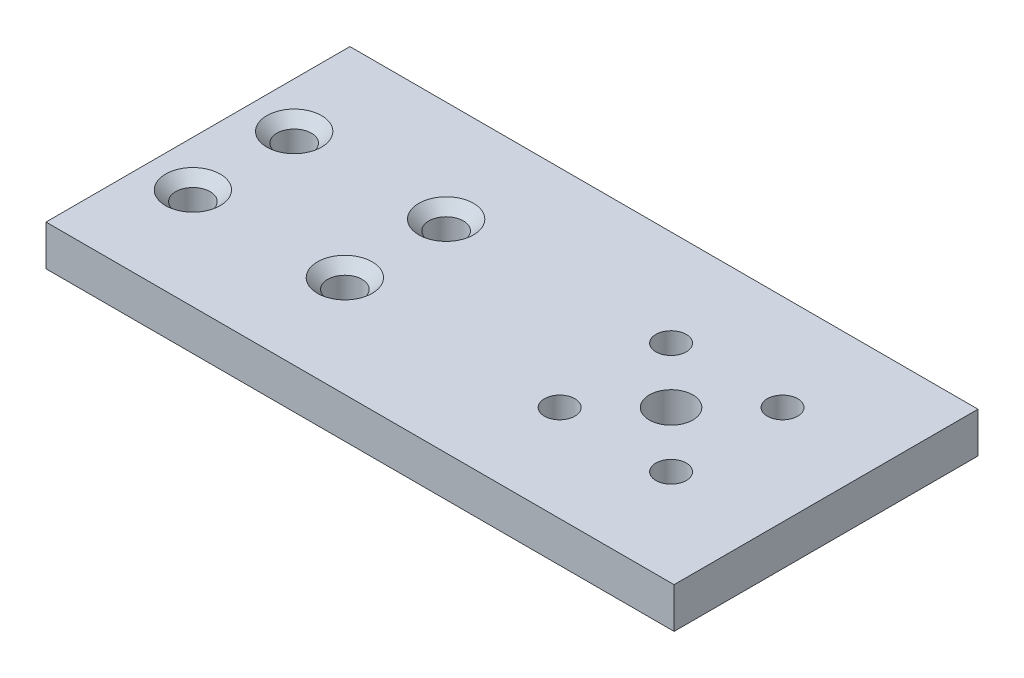
SolidWorks part; units mm, degrees
ref_plane "Front Plane" through (0, 0, 0) normal (0, 0, 1) x (1, 0, 0)
ref_plane "Top Plane" through (0, 0, 0) normal (0, 1, 0) x (1, 0, 0)
ref_plane "Right Plane" through (0, 0, 0) normal (1, 0, 0) x (0, 0, -1)
sketch "Sketch1" plane through (0, 0, 0) normal (0, 1, 0) x (1, 0, 0)
  line L1 (-10, 14) -> (10, 14)
  line L2 (-10, 14) -> (-10, -14)
  line L3 (-10, -14) -> (10, -14)
  line L4 (10, 14) -> (10, -14)
  line L5 (-10, 14) -> (10, -14) construction
  line L6 (-10, -14) -> (10, 14) construction
  point P0 (0, 0)
  dimension "D1" = 28
  dimension "D2" = 20
extrude "Boss-Extrude1" add sketch "Sketch1" along normal blind 4
sketch "Sketch2" plane through (0, 4, 0) normal (0, 1, 0) x (1, 0, 0)
  circle A0 centre (-7.5, 5) radius 1.7
  circle A1 centre (-7.5, -5) radius 1.7
  circle A2 centre (7.5, -5) radius 1.7
  circle A3 centre (7.5, 5) radius 1.7
  point P8 (6.085, 8.3324)
  point P9 (-14.3137, -3.976)
  point P10 (-14.3137, 11.024)
  point P11 (-14.3137, -8.7472)
  point P12 (1.6863, -8.7472)
  point P13 (-14.3137, 6.2528)
  point P14 (-14.3137, -7.5)
  point P15 (1.6863, -7.5)
  point P16 (0, 0)
  point P19 (0, 0)
  point P20 (8, 7.5)
  point P21 (8, 7.5)
  point P22 (-8, 4.9678)
  point P23 (8, 4.8577)
  point P24 (8, -5.1419)
  point P25 (8, -5.1423)
  point P26 (0, 0)
  dimension "D1" = 3.4
  dimension "D2" = 10
  dimension "D4" = 5
  dimension "D3" = 15
  dimension "D5" = 10
  dimension "D6" = 15
  dimension "D7" = 7.5
  dimension "D8" = 7.5
  dimension "D9" = 5
extrude "Cut-Extrude1" cut sketch "Sketch2" against normal blind 4 contours A2 | A1 | A3 | A0
sketch "Sketch6" plane through (0, 4, 0) normal (0, 1, 0) x (1, 0, 0)
  line L1 (10, 14) -> (50, 14)
  line L2 (10, 14) -> (10, -14)
  line L3 (10, -14) -> (50, -14)
  line L4 (50, 14) -> (50, -14)
  dimension "D1" = 40
  dimension "D2" = 28
extrude "Boss-Extrude2" add sketch "Sketch6" against normal blind 4
sketch "Sketch7" plane through (0, 4, 0) normal (0, 1, 0) x (1, 0, 0)
  line L1 (-10, 14) -> (-12, 14)
  line L2 (-10, 14) -> (-10, -14)
  line L3 (-10, -14) -> (-12, -14)
  line L4 (-12, 14) -> (-12, -14)
  dimension "D1" = 2
  dimension "D2" = 28
extrude "Boss-Extrude3" add sketch "Sketch7" against normal blind 4
chamfer "Chamfer2" distance 1 angle 45 4 edges at (-7.5, 4, 6.7) (7.5, 4, 6.7) (7.5, 4, -3.3) (-7.5, 4, -3.3)
sketch "Sketch8" plane through (0, 4, 0) normal (0, 1, 0) x (1, 0, 0)
  circle A0 centre (34.7032, 0) radius 2.15
  circle A1 centre (29.2032, 5.5) radius 1.5
  circle A2 centre (40.2032, 5.5) radius 1.5
  circle A3 centre (40.2032, -5.5) radius 1.5
  circle A4 centre (29.2032, -5.5) radius 1.5
  point P10 (0, 0)
  point P11 (0, 0)
  point P12 (0, 0)
  point P13 (0, 0)
  point P14 (34.7032, 0)
  dimension "D1" = 4.3
  dimension "D2" = 3
  dimension "D3" = 11
  dimension "D4" = 11
  dimension "D5" = 11
  dimension "D6" = 11
  dimension "D7" = 5.5
  dimension "D8" = 5.5
  dimension "D9" = 5.5
  dimension "D10" = 5.5
extrude "Cut-Extrude2" cut sketch "Sketch8" against normal blind 4
sketch "Sketch12" plane through (0, 0, 14) normal (0, 0, 1) x (1, 0, 0)
  line L4 (-12, 0) -> (50, 0)
  line L5 (50, 0) -> (50, 4)
  line L6 (50, 4) -> (-12, 4)
  line L7 (-12, 4) -> (-12, 0)
  line L8 (-12, 0) -> (50, 0)
  line L9 (50, 0) -> (50, 4)
  line L10 (50, 4) -> (-12, 4)
  line L11 (-12, 4) -> (-12, 0)
  dimension "D1" = 0
extrude "Boss-Extrude4" add sketch "Sketch12" along normal blind 1
sketch "Sketch13" plane through (0, 0, -14) normal (0, 0, -1) x (-1, 0, 0)
  line L4 (-50, 0) -> (12, 0)
  line L5 (12, 0) -> (12, 4)
  line L6 (12, 4) -> (-50, 4)
  line L7 (-50, 4) -> (-50, 0)
  line L8 (-50, 0) -> (12, 0)
  line L9 (12, 0) -> (12, 4)
  line L10 (12, 4) -> (-50, 4)
  line L11 (-50, 4) -> (-50, 0)
  dimension "D1" = 0
extrude "Boss-Extrude5" add sketch "Sketch13" along normal blind 1
